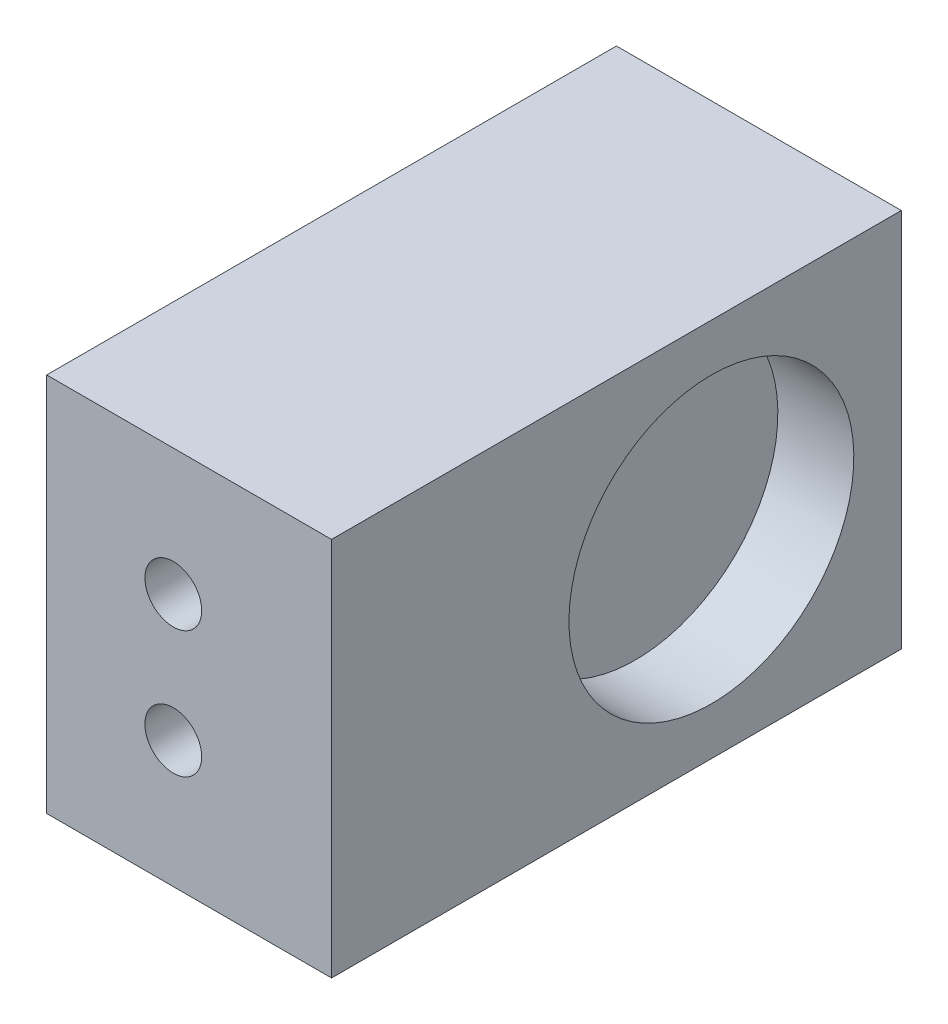
SolidWorks part; units mm, degrees
material "6061 Alloy"
ref_plane "Front" through (0, 0, 0) normal (0, 0, 1) x (1, 0, 0)
ref_plane "Top" through (0, 0, 0) normal (0, 1, 0) x (1, 0, 0)
ref_plane "Right" through (0, 0, 0) normal (1, 0, 0) x (0, 0, -1)
sketch "Sketch1" plane through (0, 0, 0) normal (0, 0, 1) x (1, 0, 0)
  line L1 (0, 0) -> (-19.05, 0)
  line L2 (0, 0) -> (0, 25.4)
  line L3 (0, 25.4) -> (-19.05, 25.4)
  line L4 (-19.05, 0) -> (-19.05, 25.4)
  dimension "D1" = 19.05
  dimension "D2" = 25.4
extrude "Boss-Extrude1" add sketch "Sketch1" along normal blind 38.1
hole_wizard "Tap Drill for #10-24 Tap1" positions "Sketch5" profile "Sketch6" hole size "#10-24" standard "ANSI Inch"
sketch "Sketch5" plane through (0, 0, 38.1) normal (0, 0, 1) x (1, 0, 0)
  line L0 (-19.05, 25.4) -> (-19.05, 0) construction
  line L1 (0, 25.4) -> (-19.05, 25.4) construction
  line L3 (-19.05, 0) -> (0, 0) construction
  point P0 (-10.5833, 16.9333)
  point P2 (-10.5833, 8.4667)
  dimension "D1" = 8.4667
  dimension "D2" = 8.4667
  dimension "D3" = 8.4667
  dimension "D4" = 8.4667
sketch "Sketch6" plane through (-10.5833, 16.9333, 38.1) normal (1, 0, 0) x (0, -1, 0)
  line L0 (0, 0) -> (0, 20.1908)
  line L1 (0, 20.1908) -> (1.8986, 19.05)
  line L2 (1.8986, 19.05) -> (1.8986, 0)
  line L5 (1.8986, 0) -> (0, 0)
  line L10 (0, 20.1908) -> (-1.8987, 19.05) construction
  line L11 (0, -6.35) -> (0, 107.95) construction
  dimension "Hole Dia." = 3.7973
  dimension "Hole Depth" = 19.05
  dimension "Drill Angle" = 118
sketch "Sketch7" plane through (0, 0, 0) normal (1, 0, 0) x (0, 0, -1)
  line L0 (0, 0) -> (0, 25.4) construction
  line L1 (-38.1, 25.4) -> (0, 25.4) construction
  circle A0 centre (-12.7, 12.7) radius 9.525
  dimension "D1" = 12.7
  dimension "D2" = 19.05
  dimension "D3" = 12.7
extrude "Cut-Extrude1" cut sketch "Sketch7" against normal blind 5.08
